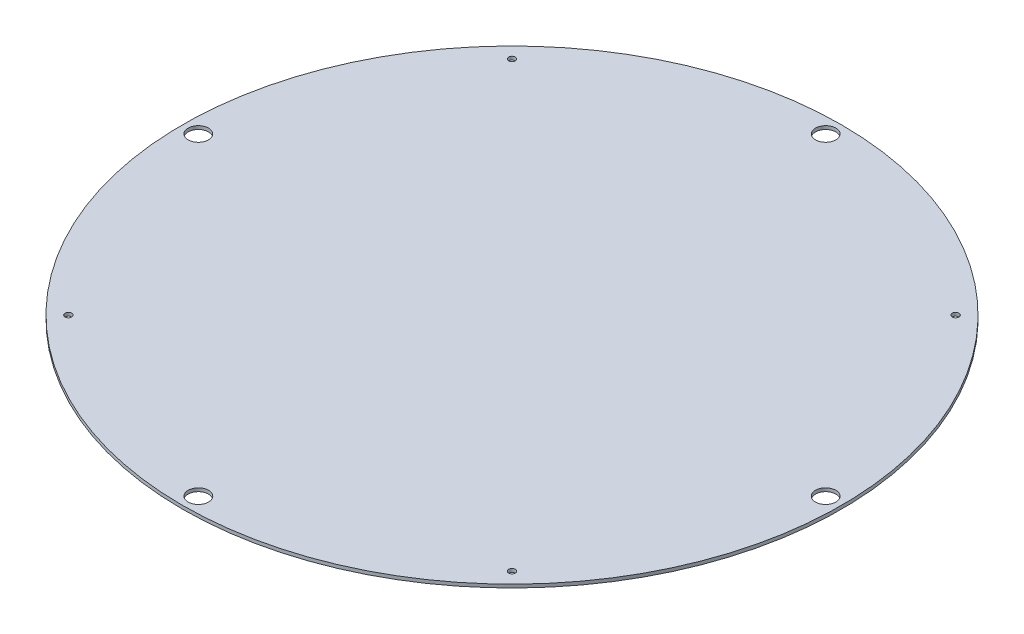
SolidWorks part; units mm, degrees
ref_plane "Front Plane" through (0, 0, 0) normal (0, 0, 1) x (1, 0, 0)
ref_plane "Top Plane" through (0, 0, 0) normal (0, 1, 0) x (1, 0, 0)
ref_plane "Right Plane" through (0, 0, 0) normal (1, 0, 0) x (0, 0, -1)
sketch "Sketch1" plane through (0, 265.6641, 0) normal (0, 1, 0) x (1, 0, 0)
  circle A0 centre (394.0867, -1220.0625) radius 5.1 construction
  circle A1 centre (581.5867, -1032.5625) radius 5.1 construction
  circle A2 centre (394.0867, -845.0625) radius 5.1 construction
  circle A3 centre (206.5867, -1032.5625) radius 5.1 construction
  circle A4 centre (394.0867, -1032.5625) radius 198 construction
  circle A5 centre (394.0867, -1220.0625) radius 5.1 construction
  circle A6 centre (581.5867, -1032.5625) radius 5.1 construction
  circle A7 centre (394.0867, -845.0625) radius 5.1 construction
  circle A8 centre (206.5867, -1032.5625) radius 5.1 construction
  circle A9 centre (394.0867, -1032.5625) radius 198 construction
  circle A11 centre (261.5041, -1165.145) radius 1.5
  circle A12 centre (261.5041, -1165.145) radius 1.5 construction
  circle A13 centre (526.6692, -1165.145) radius 1.5
  circle A14 centre (526.6692, -1165.145) radius 1.5 construction
  circle A15 centre (526.6692, -899.9799) radius 1.5
  circle A16 centre (526.6692, -899.9799) radius 1.5 construction
  circle A17 centre (261.5041, -899.9799) radius 1.5
  circle A18 centre (261.5041, -899.9799) radius 1.5 construction
  circle A22 centre (394.0867, -1032.5625) radius 197
  circle A23 centre (394.0867, -845.0625) radius 6.1
  circle A24 centre (394.0867, -1220.0625) radius 6.1
  circle A25 centre (581.5867, -1032.5625) radius 6.1
  circle A27 centre (261.5041, -899.9799) radius 2
  circle A28 centre (526.6692, -899.9799) radius 2
  circle A29 centre (526.6692, -1165.145) radius 2
  circle A30 centre (261.5041, -1165.145) radius 2
  circle A31 centre (206.5867, -1032.5625) radius 6.1
  dimension "D5" = 1
  dimension "D6" = 1
  dimension "D7" = 1
  dimension "D8" = 1
  dimension "D9" = 1
  dimension "D10" = 0.5
  dimension "D11" = 0.5
  dimension "D12" = 0.5
  dimension "D13" = 0.5
  dimension "D1" = 0
  dimension "D2" = 0
  dimension "D3" = 0
  dimension "D4" = 0
extrude "Boss-Extrude1" add sketch "Sketch1" along normal blind 2
